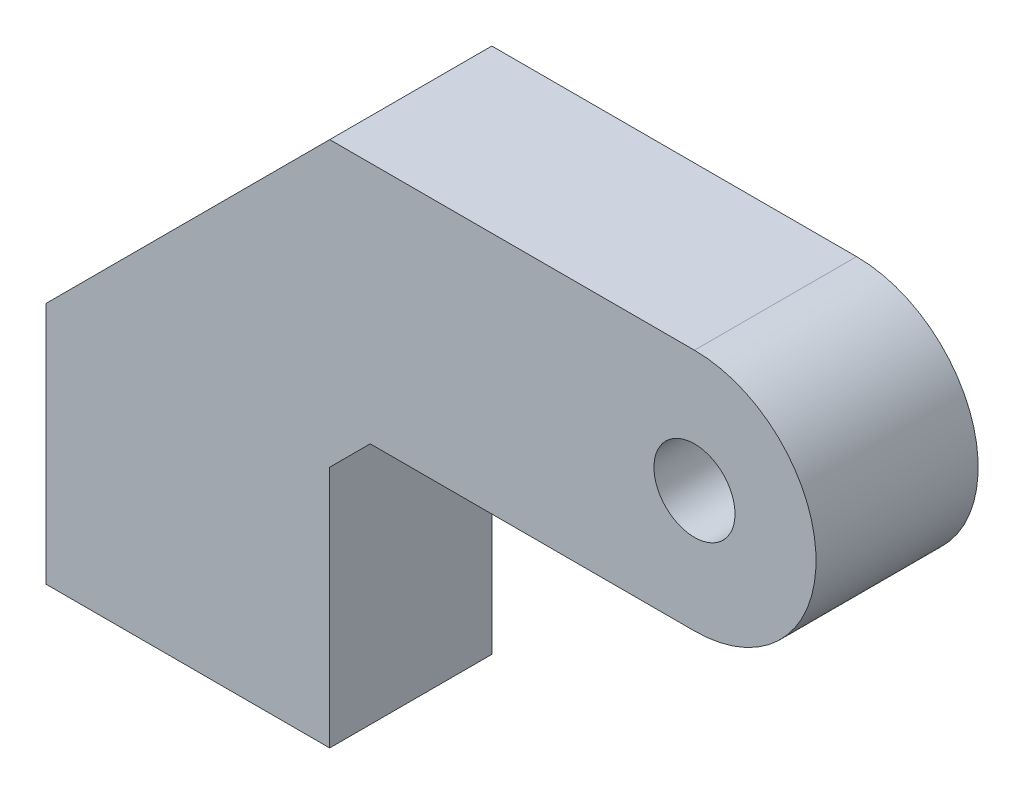
SolidWorks part; units mm, degrees
ref_plane "Front" through (0, 0, 0) normal (0, 0, 1) x (1, 0, 0)
ref_plane "Top" through (0, 0, 0) normal (0, 1, 0) x (1, 0, 0)
ref_plane "Right" through (0, 0, 0) normal (1, 0, 0) x (0, 0, -1)
sketch "Esquisse1" plane through (0, 0, 0) normal (0, 0, 1) x (1, 0, 0)
  line L0 (-7, 0) -> (7, 0)
  line L1 (7, 0) -> (7, 26)
  line L2 (7, 26) -> (-7, 26)
  line L3 (-7, 0) -> (-7, 26)
  line L4 (0, 26) -> (0, 0) construction
  dimension "D1" = 14
  dimension "D2" = 26
extrude "Boss.-Extru.1" add sketch "Esquisse1" along normal blind 8
sketch "Esquisse3" plane through (0, 0, 0) normal (0, -1, 0) x (-1, 0, 0)
  line L0 (0, 0) -> (0, -8) construction
  line L1 (7, -8) -> (-7, -8) construction
  line L2 (4, -4) -> (0, -4) construction
  circle A0 centre (4, -4) radius 1.25
  circle A1 centre (-4, -4) radius 1.25
  dimension "D1" = 2.5
  dimension "D2" = 8
extrude "Enlèv. mat.-Extru.1" cut sketch "Esquisse3" against normal blind 10
sketch "Esquisse4" plane through (0, 0, 8) normal (0, 0, 1) x (1, 0, 0)
  line L1 (7, 26) -> (31, 26)
  line L2 (7, 26) -> (7, 14)
  line L3 (7, 14) -> (31, 14)
  line L4 (31, 26) -> (31, 14)
  dimension "D1" = 12
  dimension "D2" = 24
extrude "Boss.-Extru.2" add sketch "Esquisse4" against normal up to vertex (8 mm away) up to point (7, 26, 0)
sketch "Esquisse5" plane through (0, 0, 8) normal (0, 0, 1) x (1, 0, 0)
  line L0 (31, 20) -> (25, 20) construction
  line L1 (31, 14) -> (31, 26) construction
  line L2 (-7, 26) -> (-7, 0) construction
  circle A0 centre (25, 20) radius 2
  dimension "D1" = 4
  dimension "D2" = 32
extrude "Enlèv. mat.-Extru.2" cut sketch "Esquisse5" against normal through all
chamfer "Chanfrein1" distance 14 angle 45 1 edges at (-7, 26, 4)
sketch "Esquisse6" plane through (0, 0, 8) normal (0, 0, 1) x (1, 0, 0)
  line L0 (31, 26) -> (7, 26) construction
  line L1 (7, 14) -> (31, 14) construction
  line L2 (25, 14) -> (25, 20) construction
  line L3 (25, 20) -> (25, 26) construction
  line L4 (31, 20) -> (31, 14) construction
  line L5 (25, 26) -> (32, 26)
  line L6 (32, 26) -> (32, 14)
  line L7 (32, 14) -> (25, 14)
  arc A0 (25, 26) -> (25, 14) centre (25, 20) cw
  dimension "D1" = 1
extrude "Enlèv. mat.-Extru.3" cut sketch "Esquisse6" against normal through all
chamfer "Chanfrein2" distance 2 angle 45 1 edges at (7, 14, 4)
